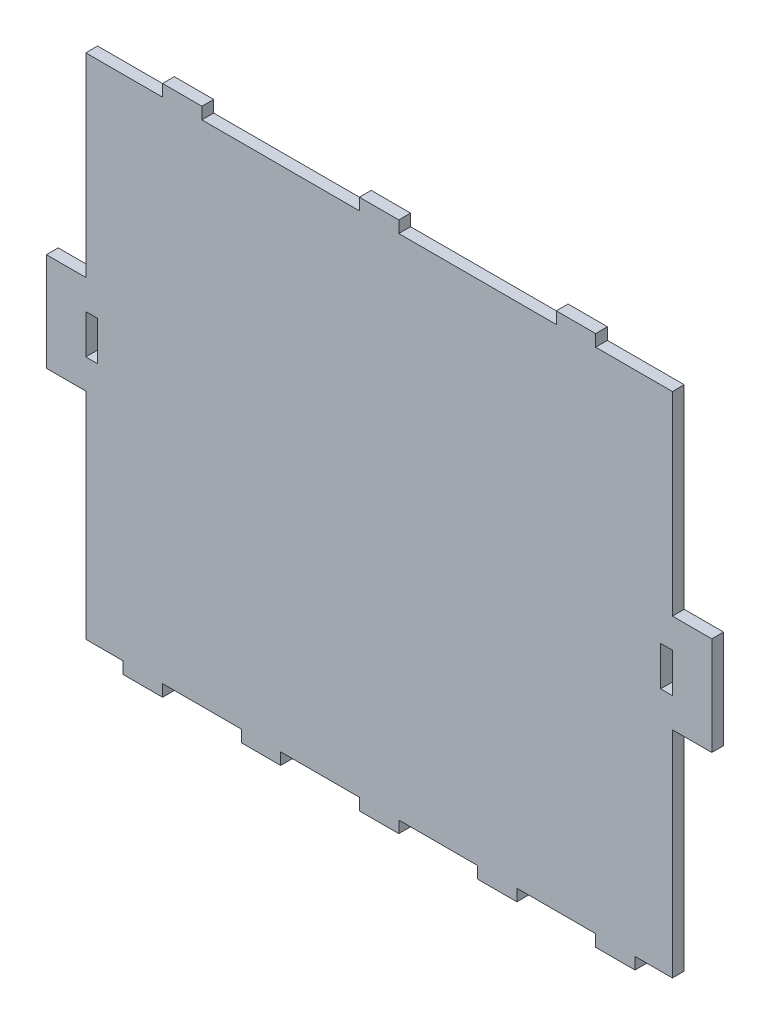
SolidWorks part; units mm, degrees
ref_plane "Front Plane" through (0, 0, 0) normal (0, 0, 1) x (1, 0, 0)
ref_plane "Top Plane" through (0, 0, 0) normal (0, 1, 0) x (1, 0, 0)
ref_plane "Right Plane" through (0, 0, 0) normal (1, 0, 0) x (0, 0, -1)
sketch "Sketch1" plane through (0, 0, 0) normal (0, 0, 1) x (1, 0, 0)
  line L0 (-74.5, 61.9) -> (-55, 61.9)
  line L1 (-55, 61.9) -> (-55, 64.9)
  line L2 (-55, 64.9) -> (-45, 64.9)
  line L3 (-45, 64.9) -> (-45, 61.9)
  line L4 (-45, 61.9) -> (-5, 61.9)
  line L5 (-5, 61.9) -> (-5, 64.9)
  line L6 (-5, 64.9) -> (5, 64.9)
  line L7 (5, 64.9) -> (5, 61.9)
  line L8 (5, 61.9) -> (45, 61.9)
  line L9 (45, 61.9) -> (45, 64.9)
  line L10 (45, 64.9) -> (55, 64.9)
  line L11 (55, 64.9) -> (55, 61.9)
  line L12 (55, 61.9) -> (74.5, 61.9)
  line L13 (74.5, 61.9) -> (74.5, 12.5)
  line L14 (74.5, 12.5) -> (84.5, 12.5)
  line L15 (84.5, 12.5) -> (84.5, -12.5)
  line L16 (84.5, -12.5) -> (74.5, -12.5)
  line L17 (74.5, -12.5) -> (74.5, -67.1)
  line L18 (74.5, -67.1) -> (65, -67.1)
  line L19 (65, -67.1) -> (65, -70.1)
  line L20 (65, -70.1) -> (55, -70.1)
  line L21 (55, -70.1) -> (55, -67.1)
  line L22 (55, -67.1) -> (35, -67.1)
  line L23 (35, -70.1) -> (25, -70.1)
  line L24 (25, -70.1) -> (25, -67.1)
  line L25 (25, -67.1) -> (5, -67.1)
  line L26 (5, -67.1) -> (5, -70.1)
  line L27 (5, -70.1) -> (-5, -70.1)
  line L28 (-5, -70.1) -> (-5, -67.1)
  line L29 (-5, -67.1) -> (-25, -67.1)
  line L30 (-25, -67.1) -> (-25, -70.1)
  line L31 (-25, -70.1) -> (-35, -70.1)
  line L32 (-35, -70.1) -> (-35, -67.1)
  line L33 (35, -70.1) -> (35, -67.1)
  line L34 (-35, -67.1) -> (-55, -67.1)
  line L35 (-55, -67.1) -> (-55, -70.1)
  line L36 (-55, -70.1) -> (-65, -70.1)
  line L37 (-65, -70.1) -> (-65, -67.1)
  line L38 (-65, -67.1) -> (-74.5, -67.1)
  line L39 (-74.5, -67.1) -> (-74.5, -12.5)
  line L40 (-74.5, -12.5) -> (-84.5, -12.5)
  line L41 (-84.5, -12.5) -> (-84.5, 12.5)
  line L42 (-84.5, 12.5) -> (-74.5, 12.5)
  line L43 (-74.5, 12.5) -> (-74.5, 61.9)
  line L44 (55, 0) -> (-55, 0) construction
  line L45 (71.5, 5) -> (71.5, -5)
  line L46 (0, -55) -> (0, 55) construction
  line L47 (74.5, -5) -> (71.5, -5)
  line L48 (-74.5, 5) -> (-71.5, 5)
  line L49 (-74.5, 5) -> (-74.5, -5)
  line L50 (-74.5, -5) -> (-71.5, -5)
  line L51 (-71.5, 5) -> (-71.5, -5)
  line L52 (74.5, 5) -> (74.5, -5)
  line L53 (74.5, 5) -> (71.5, 5)
  point P12 (-71.5, 0)
  point P45 (-74.5, 0)
  point P46 (-84.5, 0)
  point P48 (0, -70.1)
  point P52 (0, 64.9)
  point P53 (-50, 64.9)
  dimension "D1" = 10
  dimension "D2" = 20
  dimension "D3" = 9.5
  dimension "D4" = 10
  dimension "D5" = 40
  dimension "D6" = 10
  dimension "D8" = 149
  dimension "D9" = 129
  dimension "D10" = 25
  dimension "D11" = 3
  dimension "D12" = 3
  dimension "D13" = 10
  dimension "D14" = 3
  dimension "49.4" = 52.4
extrude "Boss-Extrude1" add sketch "Sketch1" along normal blind 3
